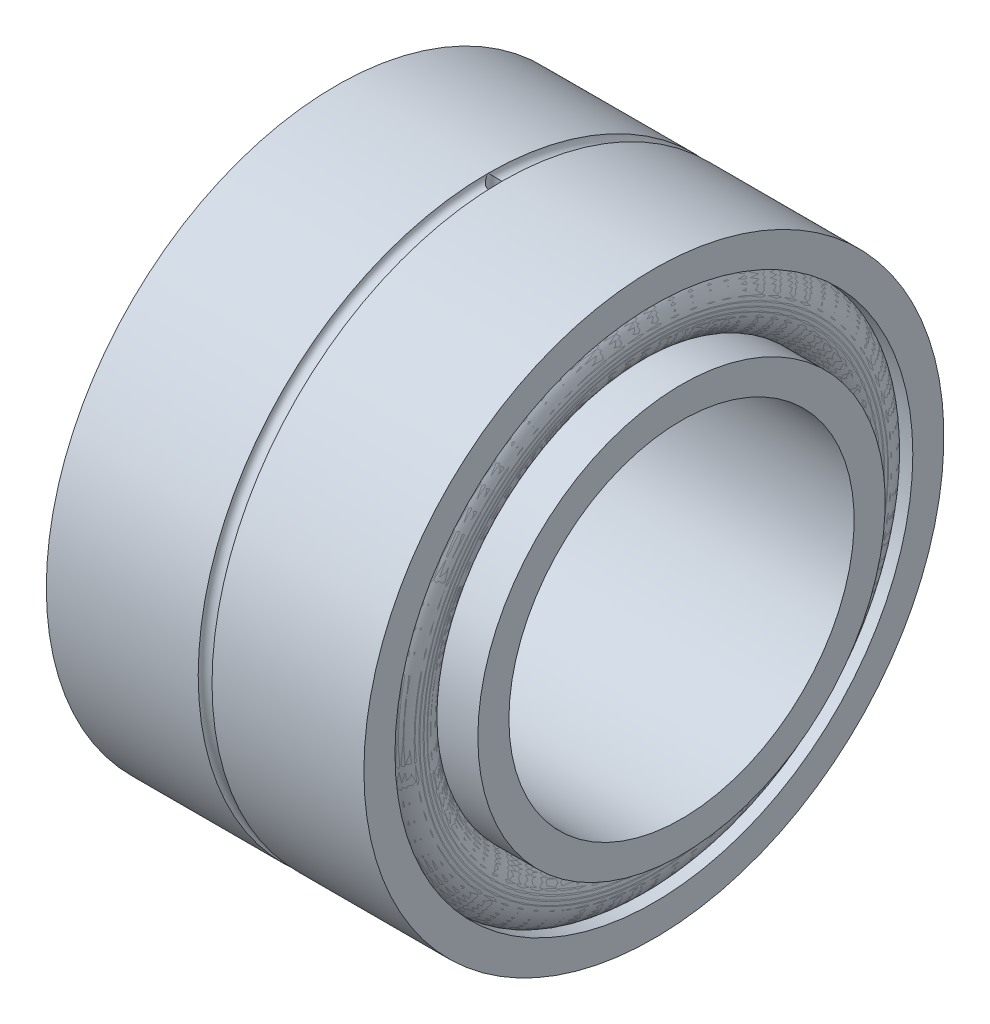
SolidWorks part; units mm, degrees
material "SKF_Blau"
ref_plane "Vorne" through (0, 0, 0) normal (0, 0, 1) x (1, 0, 0)
ref_plane "Oben" through (0, 0, 0) normal (0, 1, 0) x (1, 0, 0)
ref_plane "Rechts" through (0, 0, 0) normal (1, 0, 0) x (0, 0, -1)
sketch "Skizze1" plane through (0, 0, 0) normal (0, 0, 1) x (1, 0, 0)
  line L0 (0, 0) -> (24.5723, 0) construction
  line L1 (0, 14.75) -> (0, 12.5)
  line L2 (0, 12.5) -> (25, 12.5)
  line L3 (25, 12.5) -> (25, 14.75)
  line L4 (25, 14.75) -> (22, 14.75)
  line L5 (0, 14.75) -> (2, 14.75)
  line L6 (2, 14.75) -> (2, 18.75)
  line L7 (16.9967, 14.75) -> (16.9967, 18.75)
  line L8 (2, 16.75) -> (5.0134, 16.75) construction
  line L9 (16.9967, 14.75) -> (18.9967, 14.75)
  line L10 (0, 18.75) -> (0, 21)
  line L11 (0, 21) -> (11, 21)
  line L12 (23, 21) -> (23, 18.75)
  line L13 (23, 18.75) -> (22, 18.75)
  line L14 (0, 18.75) -> (2, 18.75)
  line L15 (12, 21) -> (23, 21)
  line L18 (16.9967, 18.75) -> (18.9967, 18.75)
  line L19 (20.4983, 16.75) -> (16.9957, 16.75) construction
  line L20 (2.01, 14.25) -> (16.9957, 14.25)
  line L21 (2.01, 14.25) -> (2.01, 19.25)
  line L22 (2.01, 19.25) -> (16.9957, 19.25)
  line L23 (16.9957, 14.25) -> (16.9957, 19.25)
  line L24 (20.4983, 16.75) -> (20.4983, 19.6259) construction
  arc A0 (18.9967, 18.75) -> (18.9967, 14.75) centre (20.4983, 16.75) ccw
  arc A1 (22, 14.75) -> (22, 18.75) centre (20.4983, 16.75) ccw
  circle A2 centre (20.4983, 16.75) radius 2.5
  arc A3 (11, 21) -> (12, 21) centre (11.5, 21) ccw
  dimension "D13" = 5
  dimension "D7" = 1
  dimension "D1" = 23
  dimension "D2" = 25
  dimension "D3" = 2
  dimension "D8" = 25
  dimension "D9" = 42
  dimension "D10" = 4
  dimension "D12" = 1
  dimension "D14" = 0.001
  dimension "D4" = 0.5
  dimension "D5" = 0.01
  dimension "D6" = 0.001
  dimension "D11" = 11.5
revolve "Rotation1" add sketch "Skizze1" angle 360 about L0
ref_plane "Ebene1" through (0, 21, 0) normal (0, 1, 0) x (1, 0, 0)
sketch "Skizze2" plane through (0, 21, 0) normal (0, 1, 0) x (1, 0, 0)
  circle A0 centre (11.5, 0) radius 0.5
  dimension "D1" = 1
  dimension "D2" = 11.5
extrude "Schnitt-Linear austragen1" cut sketch "Skizze2" against normal blind 10
equation "\"D12@Skizze1\"=\"D3@Skizze1\"/2"
